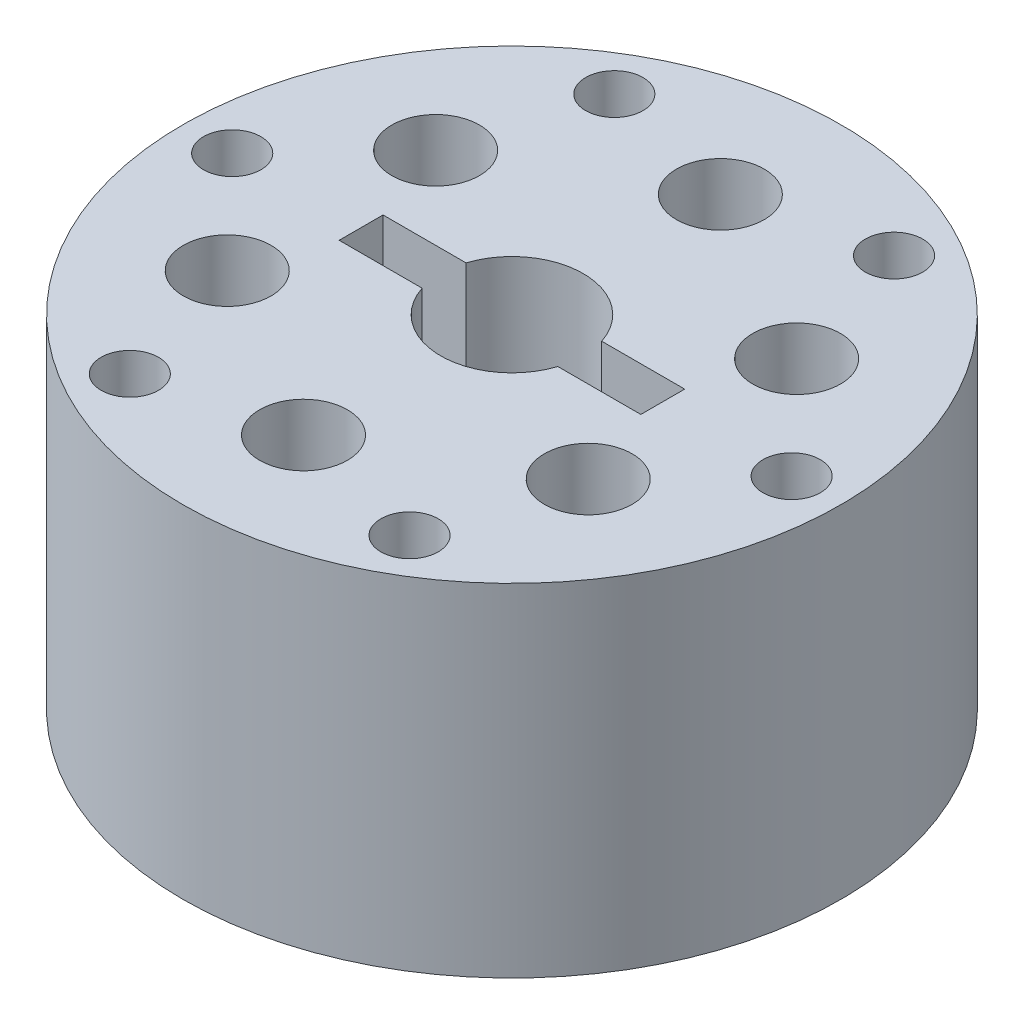
SolidWorks part; units mm, degrees
ref_plane "Front Plane" through (0, 0, 0) normal (0, 0, 1) x (1, 0, 0)
ref_plane "Top Plane" through (0, 0, 0) normal (0, 1, 0) x (1, 0, 0)
ref_plane "Right Plane" through (0, 0, 0) normal (1, 0, 0) x (0, 0, -1)
sketch "Sketch1" plane through (0, 0, 0) normal (0, 1, 0) x (1, 0, 0)
  circle A0 centre (0, 0) radius 30
  dimension "D1" = 60
extrude "Boss-Extrude1" add sketch "Sketch1" along normal blind 31.16
sketch "Sketch2" plane through (0, 31.16, 0) normal (0, 1, 0) x (1, 0, 0)
  line L0 (-6.1847, -2) -> (-13.75, -2) construction
  line L1 (-13.75, -2) -> (-13.75, 2) construction
  line L2 (-13.75, 2) -> (-6.1847, 2) construction
  line L3 (13.75, -2) -> (6.1847, -2) construction
  line L4 (6.1847, 2) -> (13.75, 2) construction
  line L5 (13.75, 2) -> (13.75, -2) construction
  line L6 (-6.1847, -2) -> (-13.75, -2)
  line L7 (-13.75, -2) -> (-13.75, 2)
  line L8 (-13.75, 2) -> (-6.1847, 2)
  line L9 (13.75, -2) -> (6.1847, -2)
  line L10 (6.1847, 2) -> (13.75, 2)
  line L11 (13.75, 2) -> (13.75, -2)
  circle A5 centre (0, 0) radius 6.5 construction
  arc A8 (-6.1847, -2) -> (6.1847, -2) centre (0, 0) ccw
  arc A9 (6.1847, 2) -> (-6.1847, 2) centre (0, 0) ccw
extrude "Cut-Extrude1" cut sketch "Sketch2" against normal offset from surface (29.16 mm away) 2 up to face at (0, 0, 30)
sketch "Sketch3" plane through (0, 31.16, 0) normal (0, 1, 0) x (1, 0, 0)
  line L0 (0, 19) -> (0, -19) construction
  line L1 (16.4545, -9.5) -> (16.4545, 9.5) construction
  line L2 (16.4545, 9.5) -> (0, 19) construction
  line L3 (0, 19) -> (-16.4545, 9.5) construction
  line L4 (-16.4545, 9.5) -> (-16.4545, -9.5) construction
  line L5 (-16.4545, -9.5) -> (0, -19) construction
  line L6 (0, -19) -> (16.4545, -9.5) construction
  circle A0 centre (0, 0) radius 16.4545 construction
  dimension "D1" = 38
hole_wizard "CBORE for M4 SHCS1" positions "Sketch4" profile "Sketch6" counterbore size "M4" standard "ANSI Metric" end condition through all
sketch "Sketch4" plane through (0, 31.16, 0) normal (0, 1, 0) x (1, 0, 0)
  point P0 (0, 19)
  point P3 (-16.4545, 9.5)
  point P6 (-16.4545, -9.5)
  point P9 (0, -19)
  point P12 (16.4545, -9.5)
  point P15 (16.4545, 9.5)
sketch "Sketch6" plane through (0, 31.16, -19) normal (1, 0, 0) x (0, 0, 1)
  line L0 (0, 0) -> (0, 31.16)
  line L1 (0, 31.16) -> (2.25, 31.16)
  line L3 (2.25, 31.16) -> (2.25, 11)
  line L4 (2.25, 11) -> (4, 11)
  line L5 (4, 11) -> (4, 0)
  line L7 (4, 0) -> (0, 0)
  line L11 (0, -6.35) -> (0, 107.95) construction
  dimension "Thru Hole Dia." = 4.5
  dimension "Thru Hole Depth" = 31.16
  dimension "C'Bore Dia." = 8
  dimension "C'Bore Depth" = 11
sketch "Sketch7" plane through (0, 31.16, 0) normal (0, 1, 0) x (1, 0, 0)
  line L0 (-30, 0) -> (-21, 0) construction
  line L1 (25.5, 0) -> (12.75, 22.0836) construction
  line L2 (12.75, 22.0836) -> (-12.75, 22.0836) construction
  line L3 (-12.75, 22.0836) -> (-25.5, 0) construction
  line L4 (-25.5, 0) -> (-12.75, -22.0836) construction
  line L5 (-12.75, -22.0836) -> (12.75, -22.0836) construction
  line L6 (12.75, -22.0836) -> (25.5, 0) construction
  circle A0 centre (0, 0) radius 22.0836 construction
  circle A1 centre (0, 0) radius 30 construction
  circle A3 centre (0, 0) radius 21 construction
  circle A4 centre (-25.5, 0) radius 2.3495
  circle A5 centre (-12.75, 22.0836) radius 2.3495
  circle A6 centre (12.75, 22.0836) radius 2.3495
  circle A7 centre (25.5, 0) radius 2.3495
  circle A8 centre (12.75, -22.0836) radius 2.3495
  circle A9 centre (-12.75, -22.0836) radius 2.3495
  dimension "D1" = 42
  dimension "D2" = 4.699
extrude "Cut-Extrude2" cut sketch "Sketch7" against normal offset from surface (29.16 mm away) 2 up to face at (0, 0, -16.75)
sketch "Sketch9" plane through (0, 31.16, 0) normal (0, 1, 0) x (1, 0, 0)
  circle A0 centre (-12.75, 22.0836) radius 2.6162
  circle A1 centre (12.75, 22.0836) radius 2.6162
  circle A2 centre (25.5, 0) radius 2.6162
  circle A3 centre (12.75, -22.0836) radius 2.6162
  circle A4 centre (-12.75, -22.0836) radius 2.6162
  circle A5 centre (-25.5, 0) radius 2.6162
  dimension "D1" = 5.2324
extrude "Cut-Extrude3" cut sketch "Sketch9" against normal blind 6.35
